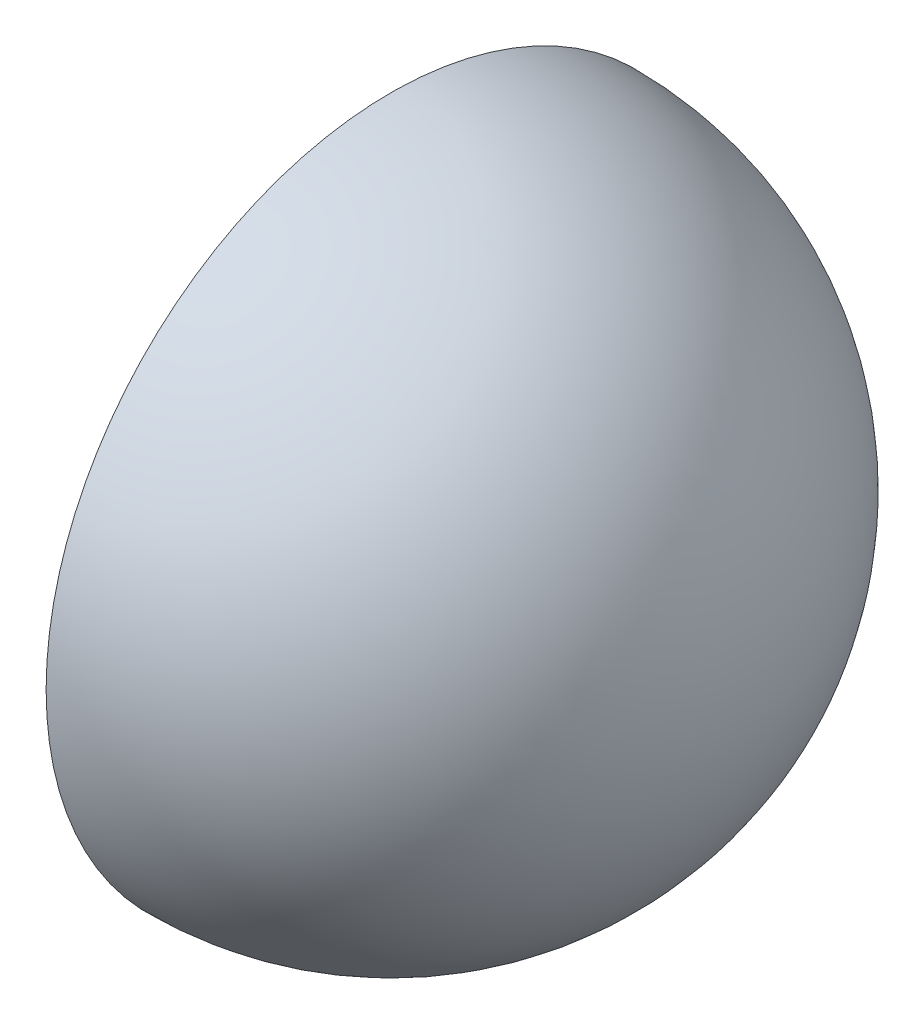
SolidWorks part; units mm, degrees
ref_plane "Спереди" through (0, 0, 0) normal (0, 0, 1) x (1, 0, 0)
ref_plane "Сверху" through (0, 0, 0) normal (0, 1, 0) x (1, 0, 0)
ref_plane "Справа" through (0, 0, 0) normal (1, 0, 0) x (0, 0, -1)
sketch "Эскиз1" plane through (0, 0, 0) normal (1, 0, 0) x (0, 0, -1)
  line L0 (0, 0) -> (0, 645.5538) construction
  line L1 (0, 240) -> (0, 250)
  line L2 (0, -250) -> (0, -240)
  arc A0 (0, 250) -> (0, -250) centre (0, 0) ccw
  arc A1 (0, 240) -> (0, -240) centre (0, 0) ccw
  dimension "D1" = 500
  dimension "D2" = 480
revolve "Повернуть3" add sketch "Эскиз1" angle 180 about L0
